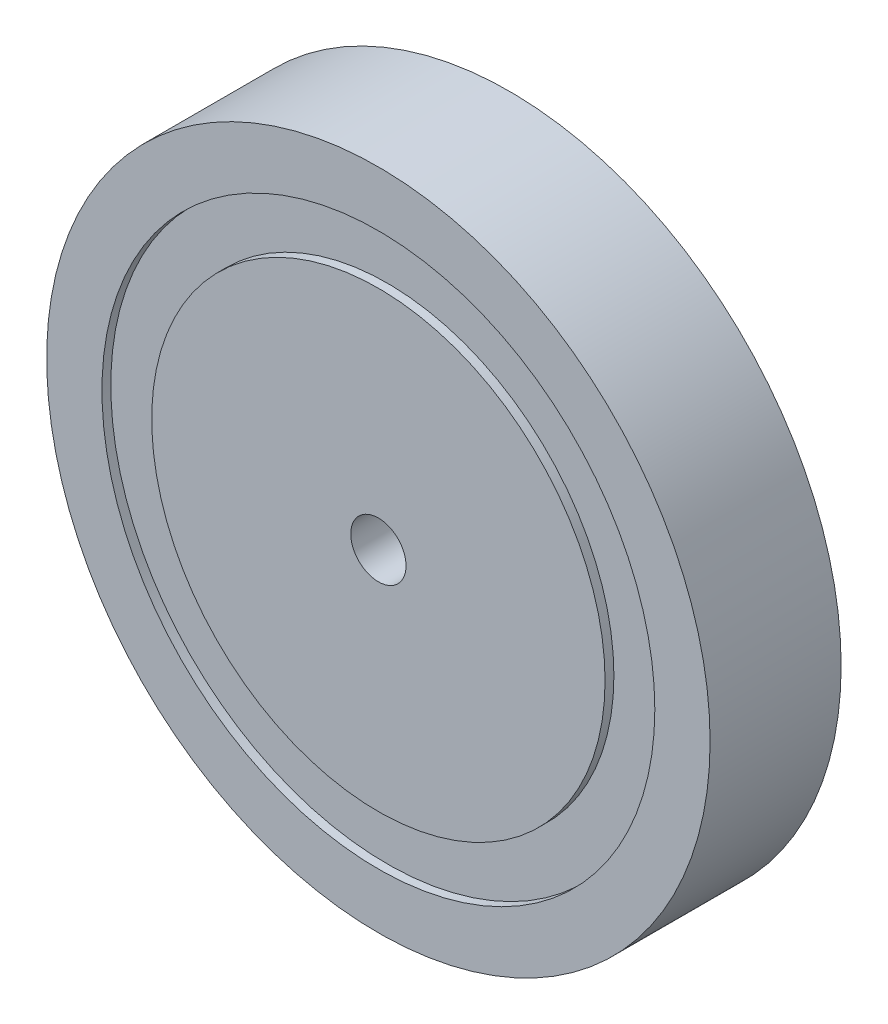
SolidWorks part; units mm, degrees
ref_plane "Front Plane" through (0, 0, 0) normal (0, 0, 1) x (1, 0, 0)
ref_plane "Top Plane" through (0, 0, 0) normal (0, 1, 0) x (1, 0, 0)
ref_plane "Right Plane" through (0, 0, 0) normal (1, 0, 0) x (0, 0, -1)
sketch "Sketch1" plane through (0, 0, 0) normal (0, 0, 1) x (1, 0, 0)
  circle A0 centre (0, 0) radius 60
  circle A1 centre (0, 0) radius 41
  circle A2 centre (0, 0) radius 5
  circle A3 centre (0, 0) radius 50
  dimension "D1" = 120
  dimension "D2" = 100
  dimension "D3" = 82
  dimension "D4" = 10
extrude "Boss-Extrude1" add sketch "Sketch1" along normal mid plane 23.7 contours A0 A3 | A3 A1 | A1 A2
sketch "Sketch2" plane through (0, 0, 11.85) normal (0, 0, 1) x (1, 0, 0)
  circle A0 centre (0, 0) radius 41
  circle A1 centre (0, 0) radius 50
  dimension "D1" = 100
  dimension "D2" = 82
extrude "Cut-Extrude1" cut sketch "Sketch2" against normal blind 1.6
sketch "Sketch3" plane through (0, 0, -11.85) normal (0, 0, -1) x (-1, 0, 0)
  circle A0 centre (0, 0) radius 24.75
  dimension "D1" = 49.5
extrude "Cut-Extrude2" cut sketch "Sketch3" against normal blind 3
